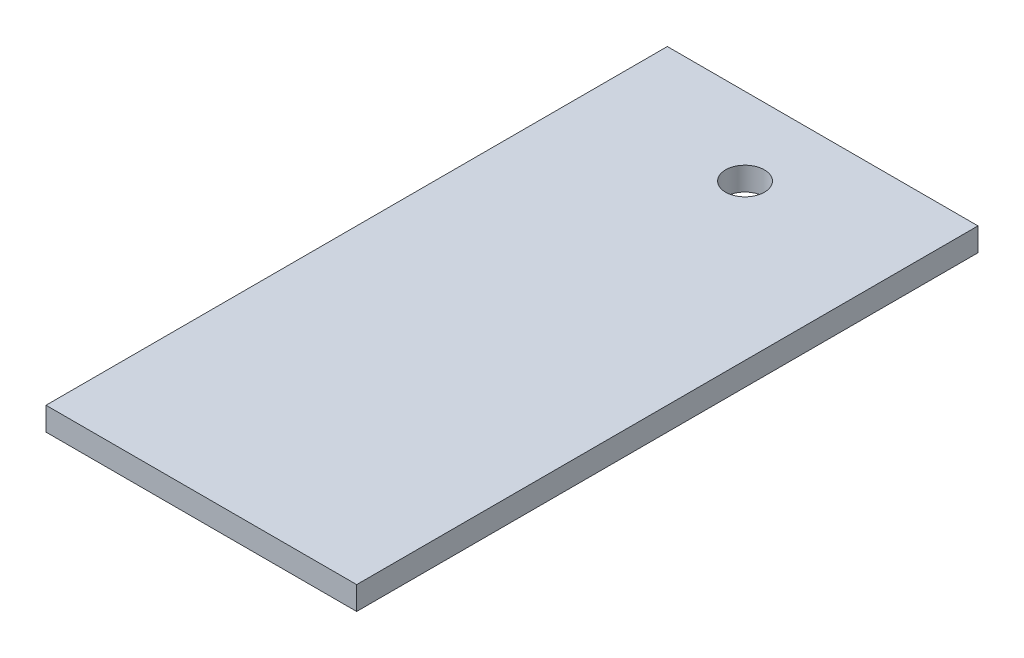
SolidWorks part; units mm, degrees
ref_plane "Front Plane" through (0, 0, 0) normal (0, 0, 1) x (1, 0, 0)
ref_plane "Top Plane" through (0, 0, 0) normal (0, 1, 0) x (1, 0, 0)
ref_plane "Right Plane" through (0, 0, 0) normal (1, 0, 0) x (0, 0, -1)
sketch "Sketch1" plane through (0, 0, 0) normal (0, 1, 0) x (1, 0, 0)
  line L2 (-20, -40) -> (20, -40)
  line L3 (-20, -40) -> (-20, 40)
  line L4 (-20, 40) -> (20, 40)
  line L5 (20, -40) -> (20, 40)
  line L6 (-20, -40) -> (20, 40) construction
  line L7 (-20, 40) -> (20, -40) construction
  point P1 (0, 0)
  dimension "D1" = 40
  dimension "D2" = 80
extrude "Boss-Extrude1" add sketch "Sketch1" along normal blind 3
sketch "Sketch2" plane through (0, 3, 0) normal (0, 1, 0) x (1, 0, 0)
  line L0 (20, -40) -> (20, 40) construction
  line L1 (20, 40) -> (-20, 40) construction
  circle A0 centre (0, 30) radius 2.5
  dimension "D1" = 5
  dimension "D2" = 20
  dimension "D3" = 10
extrude "Cut-Extrude1" cut sketch "Sketch2" against normal blind 14
